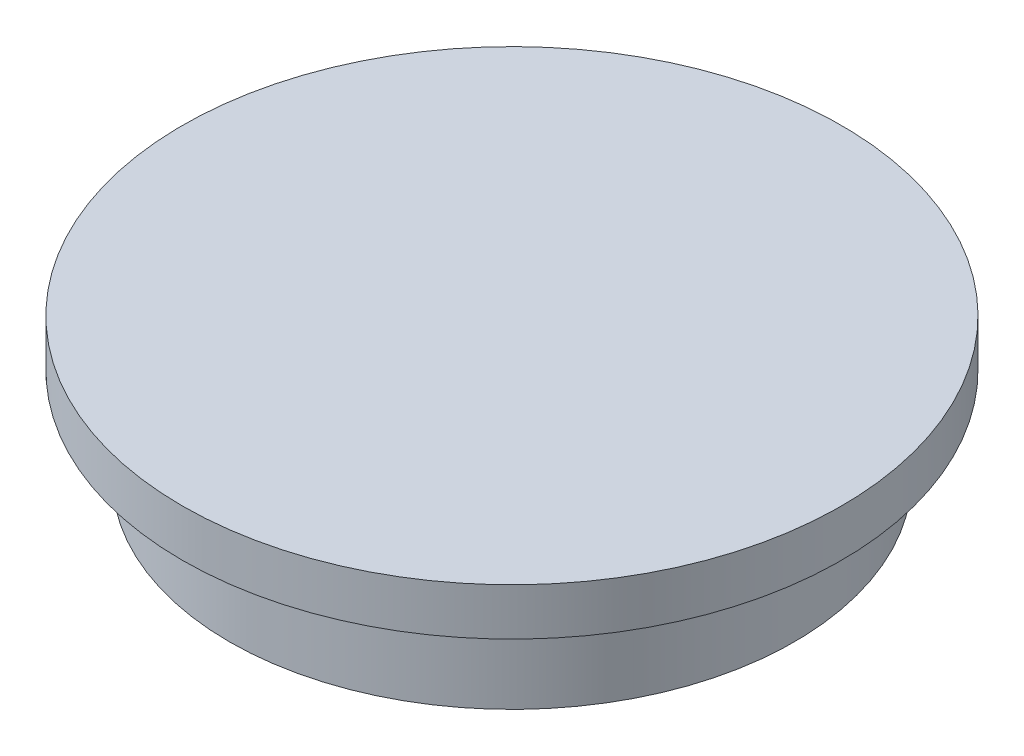
SolidWorks part; units mm, degrees
ref_plane "Front Plane" through (0, 0, 0) normal (0, 0, 1) x (1, 0, 0)
ref_plane "Top Plane" through (0, 0, 0) normal (0, 1, 0) x (1, 0, 0)
ref_plane "Right Plane" through (0, 0, 0) normal (1, 0, 0) x (0, 0, -1)
sketch "Sketch1" plane through (0, 0, 0) normal (0, 1, 0) x (1, 0, 0)
  circle A0 centre (0, 0) radius 6
  dimension "D1" = 12
extrude "Boss-Extrude1" add sketch "Sketch1" along normal blind 2
sketch "Sketch2" plane through (0, 2, 0) normal (0, 1, 0) x (1, 0, 0)
  circle A0 centre (0, 0) radius 7
  dimension "D1" = 14
extrude "Boss-Extrude2" add sketch "Sketch2" along normal blind 1
